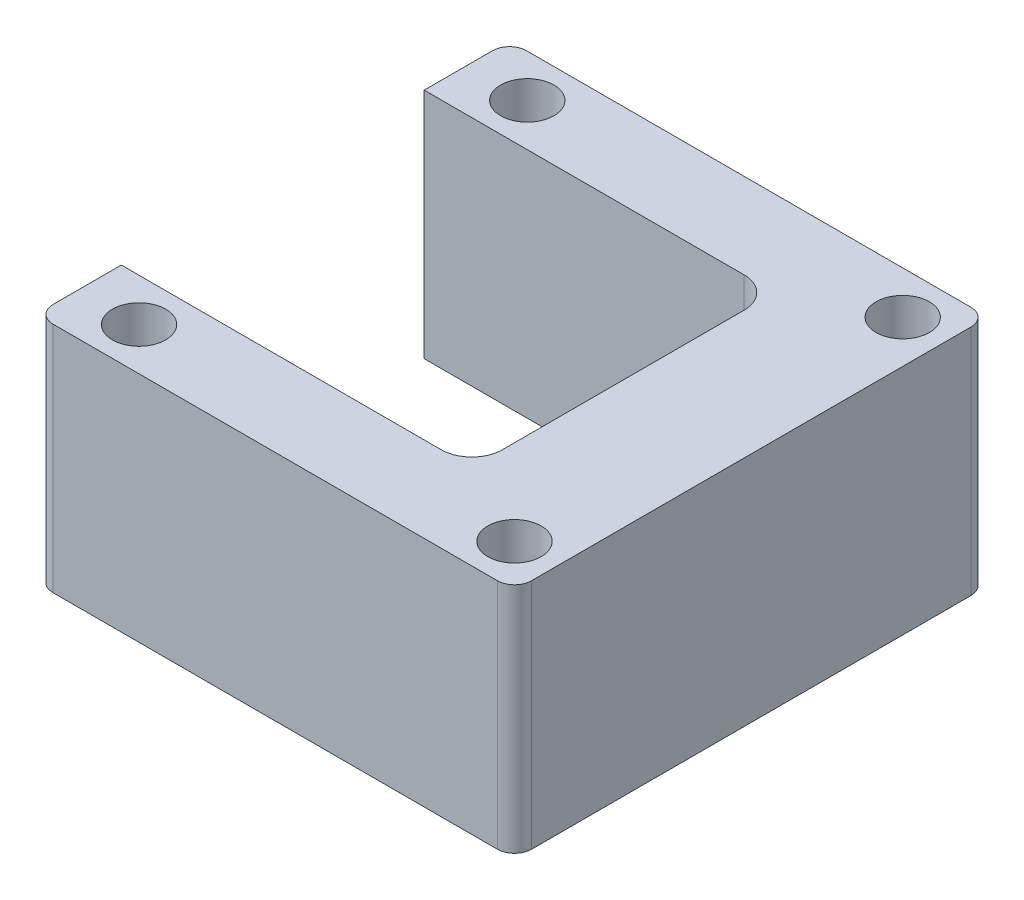
SolidWorks part; units mm, degrees
ref_plane "Front Plane" through (0, 0, 0) normal (0, 0, 1) x (1, 0, 0)
ref_plane "Top Plane" through (0, 0, 0) normal (0, 1, 0) x (1, 0, 0)
ref_plane "Right Plane" through (0, 0, 0) normal (1, 0, 0) x (0, 0, -1)
sketch "Sketch1" plane through (0, 0, 0) normal (0, 1, 0) x (1, 0, 0)
  line L0 (-79.3229, 35.2425) -> (45.1371, 35.2425)
  line L5 (45.1371, 35.2425) -> (45.1371, -35.2425)
  line L6 (45.1371, -35.2425) -> (-79.3229, -35.2425)
  line L7 (-26.0871, -22.5425) -> (26.0871, -22.5425)
  line L8 (-26.0871, -22.5425) -> (-26.0871, 22.5425)
  line L9 (-26.0871, 22.5425) -> (26.0871, 22.5425)
  line L10 (26.0871, -22.5425) -> (26.0871, 22.5425)
  line L11 (-26.0871, -22.5425) -> (26.0871, 22.5425) construction
  line L12 (-26.0871, 22.5425) -> (26.0871, -22.5425) construction
  line L13 (-79.3229, -35.2425) -> (-79.3229, 35.2425)
  line L14 (45.1371, -35.2425) -> (26.0871, -22.5425) construction
  line L15 (26.0871, 22.5425) -> (45.1371, 35.2425) construction
  line L16 (-26.0871, 22.5425) -> (-79.3229, 22.5425)
  line L17 (-26.0871, -22.5425) -> (-79.3229, -22.5425)
  line L18 (-26.0871, 35.2425) -> (-26.0871, -35.2425)
  point P0 (0, 0)
  point P4 (-72.9729, -28.8925)
  point P6 (0, 0)
  point P12 (-72.9729, 28.8925)
  point P13 (38.7871, 28.8925)
  point P14 (38.7871, -28.8925)
  point P15 (-17.0929, 28.8925)
  point P17 (-17.0929, -28.8925)
  dimension "D1" = 45.085
  dimension "D2" = 12.7
  dimension "D3" = 19.05
  dimension "D4" = 12.7
  dimension "D5" = 6.35
  dimension "D6" = 124.46
  dimension "D7" = 6.35
  dimension "D8" = 6.35
  dimension "D9" = 6.35
  dimension "D10" = 55.88
  dimension "D11" = 53.2359
extrude "Boss-Extrude2" add sketch "Sketch1" along normal blind 34.6202
hole_wizard "CBORE for #8 Socket Head Cap Screw2" positions "Sketch4" profile "Sketch5" counterbore size "#8" standard "ANSI Inch" end condition through all
sketch "Sketch4" plane through (0, 34.6202, 0) normal (0, 1, 0) x (1, 0, 0)
  point P0 (-72.9729, 28.8925)
  point P3 (38.7871, 28.8925)
  point P6 (38.7871, -28.8925)
  point P9 (-72.9729, -28.8925)
  point P12 (-17.0929, 28.8925)
  point P15 (-17.0929, -28.8925)
sketch "Sketch5" plane through (-72.9729, 34.6202, -28.8925) normal (1, 0, 0) x (0, 0, 1)
  line L0 (0, 0) -> (0, 34.6202)
  line L1 (0, 34.6202) -> (2.2479, 34.6202)
  line L3 (2.2479, 34.6202) -> (2.2479, 23.2156)
  line L4 (2.2479, 23.2156) -> (3.9687, 23.2156)
  line L5 (3.9687, 23.2156) -> (3.9687, 0)
  line L7 (3.9687, 0) -> (0, 0)
  line L11 (0, -6.35) -> (0, 107.95) construction
  dimension "Thru Hole Dia." = 4.4958
  dimension "Thru Hole Depth" = 34.6202
  dimension "C'Bore Dia." = 7.9375
  dimension "C'Bore Depth" = 23.2156
fillet "Fillet2" radius 4.5517 2 edges at (26.0871, 17.3101, 22.5425) (26.0871, 17.3101, -22.5425)
fillet "Fillet3" radius 2.54 4 edges at (45.1371, 17.3101, -35.2425) (45.1371, 17.3101, 35.2425) (-26.0871, 17.3101, 35.2425) (-26.0871, 17.3101, -35.2425)
